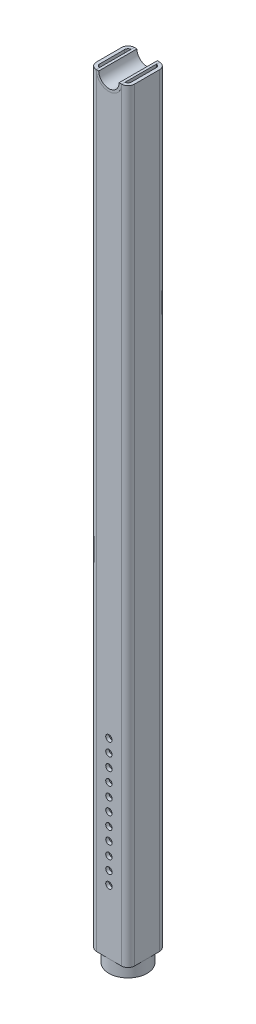
SolidWorks part; units mm, degrees
ref_plane "Front Plane" through (0, 0, 0) normal (0, 0, 1) x (1, 0, 0)
ref_plane "Top Plane" through (0, 0, 0) normal (0, 1, 0) x (1, 0, 0)
ref_plane "Right Plane" through (0, 0, 0) normal (1, 0, 0) x (0, 0, -1)
sketch "Sketch1" plane through (0, 0, 0) normal (0, 0, 1) x (1, 0, 0)
  line L0 (0, 186.5482) -> (0, -413.4518)
  point P3 (0, 0)
  dimension "D1" = 600
other "Square tube 30 X 30 X 2.6(1)"
ref_plane "Plane1" through (0, 186.5482, 0) normal (0, -1, 0) x (1, 0, 0)
sketch "Sketch11" plane through (0, 186.5482, 0) normal (0, -1, 0) x (1, 0, 0)
  line L0 (-9.8, -12.4) -> (9.8, -12.4)
  line L1 (-12.4, -9.8) -> (-12.4, 9.8)
  line L2 (9.8, 12.4) -> (-9.8, 12.4)
  line L3 (12.4, 9.8) -> (12.4, -9.8)
  line L4 (-9.8, -15) -> (9.8, -15)
  line L5 (-15, -9.8) -> (-15, 9.8)
  line L6 (9.8, 15) -> (-9.8, 15)
  line L7 (15, 9.8) -> (15, -9.8)
  arc A0 (15, 9.8) -> (9.8, 15) centre (9.8, 9.8) ccw
  arc A1 (9.8, -15) -> (15, -9.8) centre (9.8, -9.8) ccw
  arc A2 (-15, -9.8) -> (-9.8, -15) centre (-9.8, -9.8) ccw
  arc A3 (-9.8, 15) -> (-15, 9.8) centre (-9.8, 9.8) ccw
  arc A4 (-9.8, 12.4) -> (-12.4, 9.8) centre (-9.8, 9.8) ccw
  arc A5 (12.4, 9.8) -> (9.8, 12.4) centre (9.8, 9.8) ccw
  arc A6 (9.8, -12.4) -> (12.4, -9.8) centre (9.8, -9.8) ccw
  arc A7 (-12.4, -9.8) -> (-9.8, -12.4) centre (-9.8, -9.8) ccw
  point P0 (-15, 0)
  point P1 (15, 0)
  point P2 (0, 15)
  point P3 (0, -15)
  point P4 (0, 0)
  point P5 (-15, -15)
  point P6 (15, -15)
  point P7 (15, 15)
  point P8 (-15, 15)
  point P33 (0, 0)
  dimension "D1" = 5.2
  dimension "Thickness" = 2.6
  dimension "V_leg" = 30
sketch "Sketch12" plane through (0, -413.4518, 0) normal (0, -1, 0) x (1, 0, 0)
  circle A0 centre (0, 0) radius 15
  circle A1 centre (0, 0) radius 12.4
extrude "Boss-Extrude1" add sketch "Sketch12" along normal blind 10 separate body
sketch "Sketch13" plane through (0, 0, 15) normal (0, 0, 1) x (1, 0, 0)
  line L0 (0, 186.5482) -> (0, -413.4518) construction
  line L1 (9.8, -413.4518) -> (-9.8, -413.4518) construction
  circle A0 centre (0, -363.4518) radius 2.5
  dimension "D1" = 50
extrude "Cut-Extrude1" cut sketch "Sketch13" against normal through all both and the other way through all
pattern_linear "LPattern1" count 11 spacing 10 along (0, 1, 0) of "Cut-Extrude1"
sketch "Sketch14" plane through (0, 0, 15) normal (0, 0, 1) x (1, 0, 0)
  circle A0 centre (0, 186.5482) radius 10
extrude "Cut-Extrude3" cut sketch "Sketch14" against normal blind 43
sketch "Sketch15" plane through (0, 0, 15) normal (0, 0, 1) x (1, 0, 0)
  line L0 (-10.0009, 186.5482) -> (-8, 186.5482)
  line L1 (10.0009, 186.5482) -> (8, 186.5482)
  arc A0 (-10.0009, 186.5482) -> (10.0009, 186.5482) centre (0, 186.5482) ccw
  arc A1 (-8, 186.5482) -> (8, 186.5482) centre (0, 186.5482) ccw
extrude "Boss-Extrude2" add sketch "Sketch15" against normal up to vertex (30 mm away) separate body
